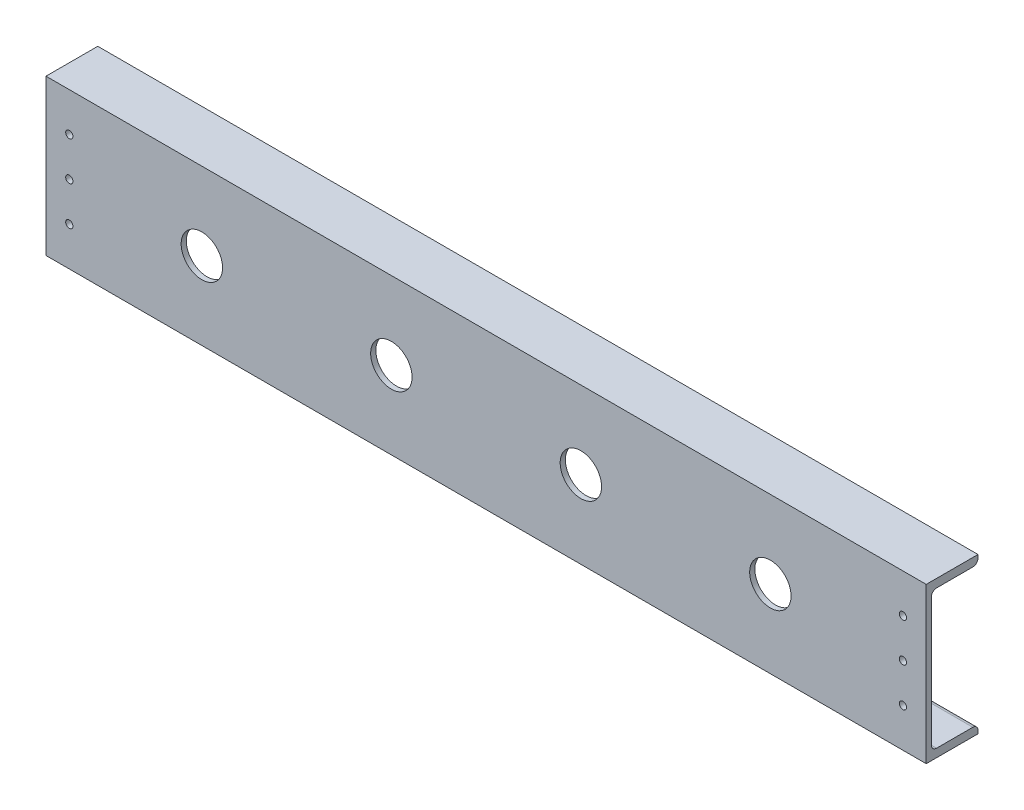
SolidWorks part; units mm, degrees
material "ASTM A36 Steel"
ref_plane "Front Plane" through (0, 0, 0) normal (0, 0, 1) x (1, 0, 0)
ref_plane "Top Plane" through (0, 0, 0) normal (0, 1, 0) x (1, 0, 0)
ref_plane "Right Plane" through (0, 0, 0) normal (1, 0, 0) x (0, 0, -1)
sketch "Sketch1" plane through (0, 0, 0) normal (1, 0, 0) x (0, 0, -1)
  line L0 (-86.6221, 113.8796) -> (-186.6221, 113.8796)
  line L1 (-186.6221, 113.8796) -> (-186.6221, -186.1204)
  line L2 (-186.6221, -186.1204) -> (-86.6221, -186.1204)
  line L3 (-86.6221, -186.1204) -> (-86.6221, -180.1204)
  line L4 (-96.6221, -170.1204) -> (-166.6221, -170.1204)
  line L5 (-176.6221, -160.1204) -> (-176.6221, 87.8796)
  line L6 (-166.6221, 97.8796) -> (-96.6221, 97.8796)
  line L7 (-86.6221, 107.8796) -> (-86.6221, 113.8796)
  arc A0 (-166.6221, -170.1204) -> (-176.6221, -160.1204) centre (-166.6221, -160.1204) cw
  arc A1 (-86.6221, -180.1204) -> (-96.6221, -170.1204) centre (-96.6221, -180.1204) ccw
  arc A2 (-96.6221, 97.8796) -> (-86.6221, 107.8796) centre (-96.6221, 107.8796) ccw
  arc A3 (-176.6221, 87.8796) -> (-166.6221, 97.8796) centre (-166.6221, 87.8796) cw
  point P12 (-86.6221, -170.1204)
  point P15 (-86.6221, 97.8796)
  dimension "D7" = 10
  dimension "D1" = 300
  dimension "D2" = 100
  dimension "D3" = 100
  dimension "D4" = 10
  dimension "D5" = 16
  dimension "D6" = 16
extrude "Boss-Extrude1" add sketch "Sketch1" along normal blind 1700
sketch "Sketch3" plane through (0, 0, 186.6221) normal (0, 0, 1) x (1, 0, 0)
  line L0 (1700, 113.8796) -> (0, 113.8796) construction
  line L1 (1700, 113.8796) -> (1700, -186.1204) construction
  circle A0 centre (1655, 38.8796) radius 7
  circle A1 centre (1655, -36.1204) radius 7
  circle A2 centre (1655, -111.1204) radius 7
  dimension "D1" = 14
  dimension "D2" = 14
  dimension "D3" = 14
  dimension "D4" = 75
  dimension "D5" = 75
  dimension "D6" = 75
  dimension "D7" = 45
  dimension "D8" = 45
extrude "Cut-Extrude1" cut sketch "Sketch3" against normal blind 10
ref_plane "Plane1" through (850, 0, 0) normal (1, 0, 0) x (0, 0, -1)
mirror "Mirror1" about plane through (850, 0, 0) normal (1, 0, 0) of "Cut-Extrude1"
sketch "Sketch5" plane through (0, 0, 176.6221) normal (0, 0, -1) x (-1, 0, 0)
  line L0 (-1700, -160.1204) -> (-1700, 87.8796) construction
  line L1 (-1700, 113.8796) -> (0, 113.8796) construction
  circle A0 centre (-1399, -36.1204) radius 40
  dimension "D1" = 80
  dimension "D2" = 301
  dimension "D3" = 150
extrude "Cut-Extrude3" cut sketch "Sketch5" against normal blind 30
pattern_linear "LPattern2" count 4 spacing 366 along (-1, 0, 0) of "Cut-Extrude3"
